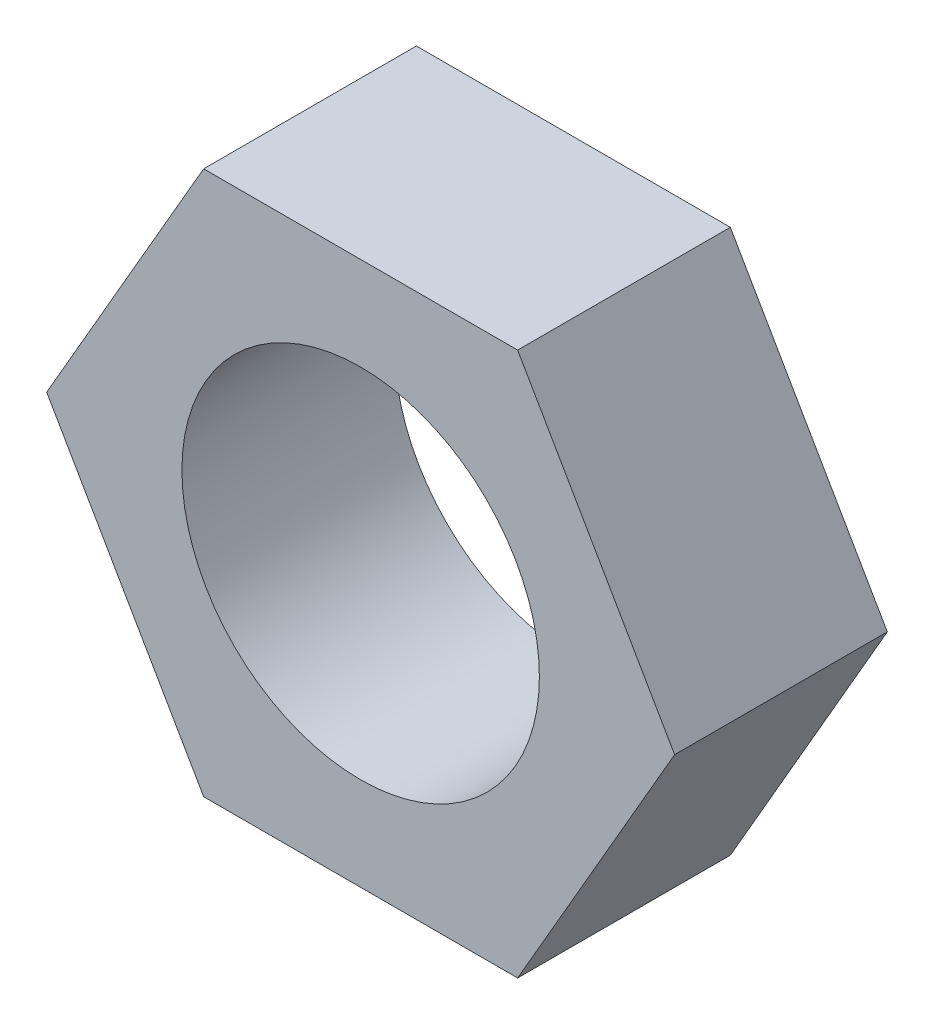
SolidWorks part; units mm, degrees
ref_plane "Plan de face" through (0, 0, 0) normal (0, 0, 1) x (1, 0, 0)
ref_plane "Plan de dessus" through (0, 0, 0) normal (0, 1, 0) x (1, 0, 0)
ref_plane "Plan de droite" through (0, 0, 0) normal (1, 0, 0) x (0, 0, -1)
sketch "Esquisse1" plane through (0, 0, 0) normal (0, 0, 1) x (1, 0, 0)
  line L1 (7.3806, 0) -> (3.6903, 6.3918)
  line L2 (3.6903, 6.3918) -> (-3.6903, 6.3918)
  line L3 (-3.6903, 6.3918) -> (-7.3806, 0)
  line L4 (-7.3806, 0) -> (-3.6903, -6.3918)
  line L5 (-3.6903, -6.3918) -> (3.6903, -6.3918)
  line L6 (3.6903, -6.3918) -> (7.3806, 0)
  circle A0 centre (0, 0) radius 6.3918 construction
  circle A1 centre (0, 0) radius 3.7067
extrude "Boss.-Extru.1" add sketch "Esquisse1" along normal blind 5 contours L3 L4 L5 L6 L1 L2
sketch "Esquisse2" plane through (0, 0, 0) normal (0, 0, -1) x (-1, 0, 0)
  circle A0 centre (0, 0) radius 4.2015
extrude "Enlèv. mat.-Extru.1" cut sketch "Esquisse2" against normal through all
